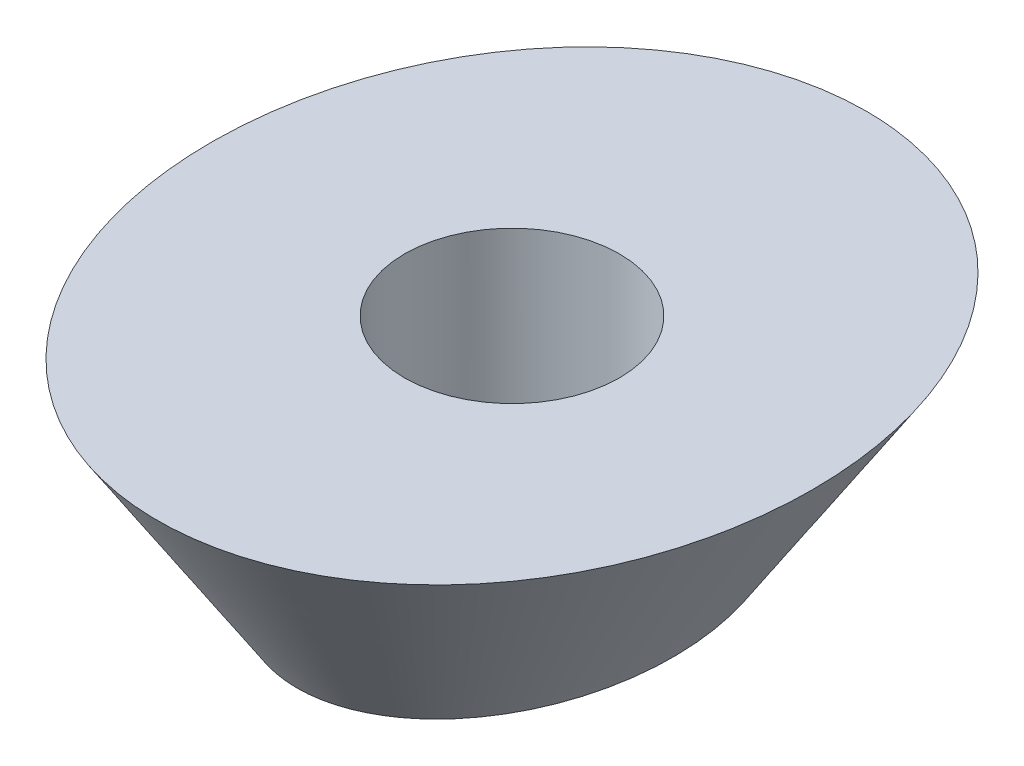
SolidWorks part; units mm, degrees
ref_plane "Front Plane" through (0, 0, 0) normal (0, 0, 1) x (1, 0, 0)
ref_plane "Top Plane" through (0, 0, 0) normal (0, 1, 0) x (1, 0, 0)
ref_plane "Right Plane" through (0, 0, 0) normal (1, 0, 0) x (0, 0, -1)
sketch "Sketch1" plane through (0, 0, 0) normal (0, 1, 0) x (1, 0, 0)
  line L0 (-3, 0) -> (3, 0) construction
  ellipse E0 centre (0, 0) end of major axis (0, 4) minor radius 3
  dimension "D3" = 8
  dimension "12" = 6
extrude "Boss-Extrude1" add sketch "Sketch1" along normal blind 4 draft 33
sketch "Sketch2" plane through (0, 0, 0) normal (0, -1, 0) x (1, 0, 0)
  circle A0 centre (0, 0) radius 2
  dimension "D1" = 4
extrude "Cut-Extrude1" cut sketch "Sketch2" against normal blind 10
